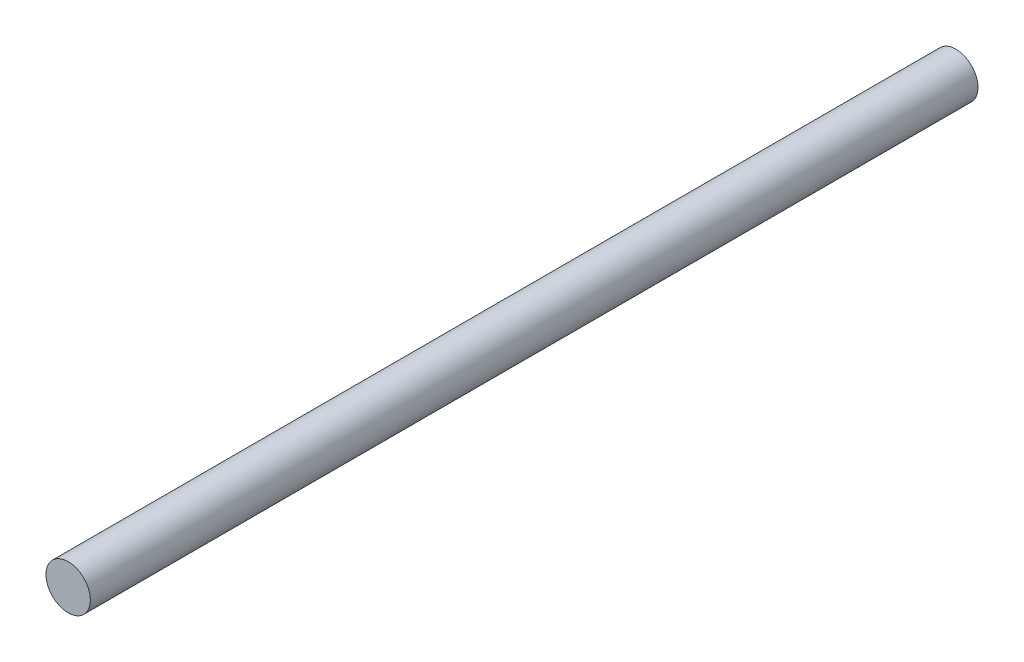
SolidWorks part; units mm, degrees
ref_plane "Front Plane" through (0, 0, 0) normal (0, 0, 1) x (1, 0, 0)
ref_plane "Top Plane" through (0, 0, 0) normal (0, 1, 0) x (1, 0, 0)
ref_plane "Right Plane" through (0, 0, 0) normal (1, 0, 0) x (0, 0, -1)
sketch "Sketch1" plane through (0, 0, 0) normal (0, 0, 1) x (1, 0, 0)
  circle A0 centre (0, 0) radius 7.5
  dimension "D1" = 15
extrude "Boss-Extrude1" add sketch "Sketch1" along normal blind 300 contours A0
